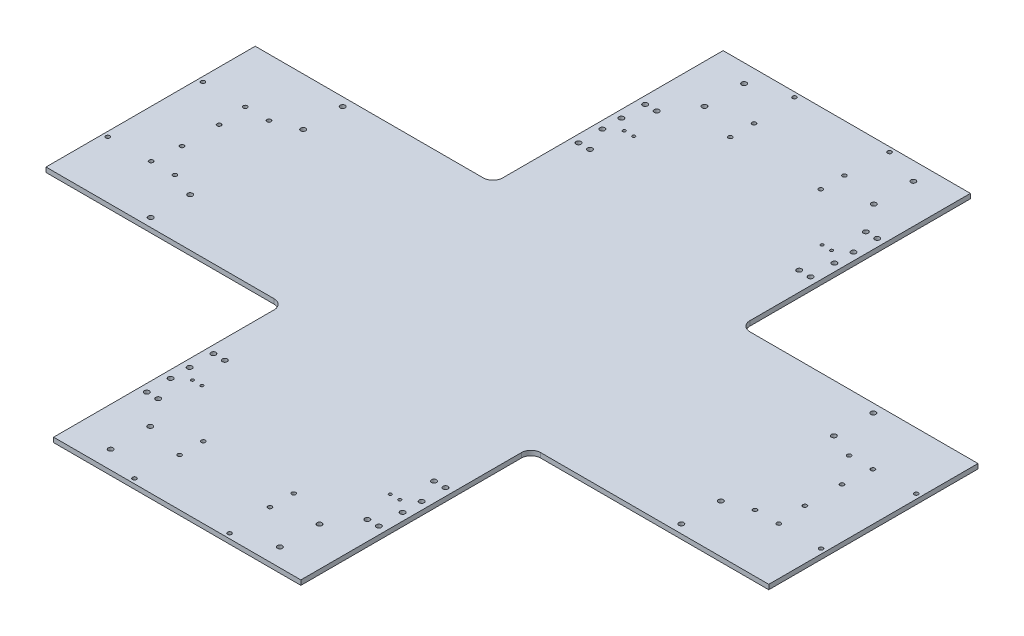
SolidWorks part; units mm, degrees
material "3.0205 (EN-AW 1200)"
ref_plane "前视基准面" through (0, 0, 0) normal (0, 0, 1) x (1, 0, 0)
ref_plane "上视基准面" through (0, 0, 0) normal (0, 1, 0) x (1, 0, 0)
ref_plane "右视基准面" through (0, 0, 0) normal (1, 0, 0) x (0, 0, -1)
other "Configuration Table"
sketch "Sketch1" plane through (0, 0, 0) normal (0, 1, 0) x (1, 0, 0)
  line L0 (130, 352) -> (-130, 352)
  line L1 (-130, 352) -> (-130, 110)
  line L2 (-130, 110) -> (-380, 110)
  line L5 (-380, 110) -> (-380, -110)
  line L6 (0, 352) -> (0, -66.8675) construction
  line L7 (-380, 0) -> (131.0517, 0) construction
  line L8 (380, 110) -> (380, -110)
  line L11 (130, 110) -> (380, 110)
  line L12 (130, 352) -> (130, 110)
  line L13 (130, -352) -> (130, -110)
  line L14 (130, -110) -> (380, -110)
  line L19 (-130, -110) -> (-380, -110)
  line L20 (-130, -352) -> (-130, -110)
  line L21 (130, -352) -> (-130, -352)
  point P21 (380, 0)
  dimension "D1" = 130
  dimension "D2" = 250
  dimension "D3" = 110
  dimension "D4" = 242
extrude "Boss-Extrude1" add sketch "Sketch1" along normal blind 5
sketch "Sketch2" plane through (0, 5, 0) normal (0, 1, 0) x (1, 0, 0)
  line L2 (380, 110) -> (130, 110) construction
  line L3 (380, -110) -> (380, 110) construction
  line L4 (-56.7455, 0) -> (47.5165, 0) construction
  line L5 (0, 54.7142) -> (0, -64.2255) construction
  line L6 (130, 110) -> (130, 352) construction
  line L7 (130, 352) -> (-130, 352) construction
  circle A0 centre (330, 49.5) radius 2.125
  circle A1 centre (305, 49.5) radius 2.125
  circle A2 centre (327.5, 19.5) radius 2.125
  circle A6 centre (327.5, -19.5) radius 2.125
  circle A7 centre (305, -49.5) radius 2.125
  circle A8 centre (330, -49.5) radius 2.125
  circle A9 centre (-330, -49.5) radius 2.125
  circle A10 centre (-305, -49.5) radius 2.125
  circle A11 centre (-327.5, -19.5) radius 2.125
  circle A12 centre (-327.5, 19.5) radius 2.125
  circle A13 centre (-305, 49.5) radius 2.125
  circle A14 centre (-330, 49.5) radius 2.125
  circle A15 centre (47.5, 302) radius 2.125
  circle A16 centre (47.5, 277) radius 2.125
  circle A17 centre (-47.5, 277) radius 2.125
  circle A18 centre (-47.5, 302) radius 2.125
  circle A19 centre (-47.5, -302) radius 2.125
  circle A20 centre (-47.5, -277) radius 2.125
  circle A21 centre (47.5, -277) radius 2.125
  circle A22 centre (47.5, -302) radius 2.125
  dimension "D1" = 60.5
  dimension "D3" = 52.5
  dimension "D5" = 4.25
  dimension "D7" = 4.25
  dimension "D8" = 4.25
  dimension "D9" = 4.25
  dimension "D10" = 4.25
  dimension "D2" = 90.5
  dimension "D4" = 25
  dimension "D6" = 50
  dimension "D11" = 82.5
  dimension "D12" = 50
  dimension "D13" = 25
extrude "Cut-Extrude1" cut sketch "Sketch2" against normal blind 3
sketch "Sketch4" plane through (0, 5, 0) normal (0, 1, 0) x (1, 0, 0)
  line L0 (-130, 352) -> (-130, 110) construction
  line L1 (130, 352) -> (-130, 352) construction
  line L2 (0, 46.9886) -> (0, -40.2904) construction
  line L3 (-35.103, 0) -> (92.4951, 0) construction
  line L5 (130, -352) -> (130, -110) construction
  circle A0 centre (-122, 192) radius 2.6
  circle A1 centre (-110, 192) radius 2.6
  circle A2 centre (-122, 217) radius 2.6
  circle A3 centre (-122, 237) radius 2.6
  circle A4 centre (-122, 262) radius 2.6
  circle A5 centre (-110, 262) radius 2.6
  circle A6 centre (110, 262) radius 2.6
  circle A7 centre (122, 262) radius 2.6
  circle A8 centre (122, 237) radius 2.6
  circle A9 centre (122, 217) radius 2.6
  circle A10 centre (110, 192) radius 2.6
  circle A11 centre (122, 192) radius 2.6
  circle A12 centre (122, -192) radius 2.6
  circle A13 centre (110, -192) radius 2.6
  circle A14 centre (122, -217) radius 2.6
  circle A15 centre (122, -237) radius 2.6
  circle A16 centre (122, -262) radius 2.6
  circle A17 centre (110, -262) radius 2.6
  circle A18 centre (-110, -262) radius 2.6
  circle A19 centre (-122, -262) radius 2.6
  circle A20 centre (-122, -237) radius 2.6
  circle A21 centre (-122, -217) radius 2.6
  circle A22 centre (-110, -192) radius 2.6
  circle A23 centre (-122, -192) radius 2.6
  circle A24 centre (109, -227) radius 1.6
  circle A25 centre (-109, -227) radius 1.6
  circle A26 centre (109, 227) radius 1.6
  circle A27 centre (-109, 227) radius 1.6
  circle A28 centre (99, -227) radius 1.6
  circle A29 centre (-99, -227) radius 1.6
  circle A30 centre (99, 227) radius 1.6
  circle A31 centre (-99, 227) radius 1.6
  dimension "D3" = 5.2
  dimension "D4" = 5.2
  dimension "D5" = 8
  dimension "D6" = 8
  dimension "D9" = 5.2
  dimension "D10" = 5.2
  dimension "D11" = 5.2
  dimension "D12" = 5.2
  dimension "D19" = 3.2
  dimension "D20" = 21
  dimension "D21" = 10
  dimension "D22" = 3.2
  dimension "D23" = 10
  dimension "D1" = 8
  dimension "D2" = 20
  dimension "D7" = 8
  dimension "D8" = 20
  dimension "D13" = 25
  dimension "D14" = 20
  dimension "D15" = 25
  dimension "D16" = 25
  dimension "D17" = 90
  dimension "D18" = 0
extrude "Cut-Extrude3" cut sketch "Sketch4" against normal blind 10
sketch "Sketch5" plane through (0, 5, 0) normal (0, 1, 0) x (1, 0, 0)
  line L0 (130, 352) -> (-130, 352) construction
  line L2 (-130, 352) -> (-130, 110) construction
  line L4 (130, 110) -> (130, 352) construction
  line L5 (-46.9195, 0) -> (66.6223, 0) construction
  line L6 (0, 59.0569) -> (0, -54.4849) construction
  line L10 (-380, 110) -> (-380, -110) construction
  line L12 (-130, 110) -> (-380, 110) construction
  line L13 (-380, -110) -> (-130, -110) construction
  circle A0 centre (-50, 347) radius 2.1
  circle A1 centre (50, 347) radius 2.1
  circle A2 centre (50, -347) radius 2.1
  circle A3 centre (-50, -347) radius 2.1
  circle A4 centre (-375, 50) radius 2.1
  circle A5 centre (-375, -50) radius 2.1
  circle A6 centre (375, -50) radius 2.1
  circle A7 centre (375, 50) radius 2.1
  dimension "D1" = 4.2
  dimension "D2" = 4.2
  dimension "D3" = 60
  dimension "D6" = 4.2
  dimension "D7" = 4.2
  dimension "5" = 5
  dimension "D4" = 80
  dimension "D5" = 80
  dimension "D8" = 60
  dimension "D9" = 5
  dimension "D10" = 5
extrude "Cut-Extrude4" cut sketch "Sketch5" against normal blind 10
fillet "Fillet1" radius 10 4 edges at (-130, 2.5, -110) (-130, 2.5, 110) (130, 2.5, 110) (130, 2.5, -110)
sketch "Sketch6" plane through (0, 5, 0) normal (0, 1, 0) x (1, 0, 0)
  line L0 (130, 352) -> (-130, 352) construction
  line L2 (130, 120) -> (130, 352) construction
  line L3 (-64.416, 0) -> (103.2752, 0) construction
  line L4 (0, 86.0771) -> (0, -73.7041) construction
  line L5 (380, 110) -> (140, 110) construction
  line L6 (380, -110) -> (380, 110) construction
  circle A0 centre (89, 333) radius 2.6
  circle A1 centre (89, 291.4) radius 2.6
  circle A2 centre (89, -291.4) radius 2.6
  circle A3 centre (89, -333) radius 2.6
  circle A4 centre (-89, -333) radius 2.6
  circle A5 centre (-89, -291.4) radius 2.6
  circle A6 centre (-89, 291.4) radius 2.6
  circle A7 centre (-89, 333) radius 2.6
  circle A8 centre (279, 101) radius 2.6
  circle A9 centre (279, 59.4) radius 2.6
  circle A10 centre (279, -59.4) radius 2.6
  circle A11 centre (279, -101) radius 2.6
  circle A12 centre (-279, -101) radius 2.6
  circle A13 centre (-279, -59.4) radius 2.6
  circle A14 centre (-279, 59.4) radius 2.6
  circle A15 centre (-279, 101) radius 2.6
  dimension "D1" = 5.2
  dimension "D2" = 5.2
  dimension "D6" = 5.2
  dimension "D7" = 5.2
  dimension "D3" = 19
  dimension "D4" = 41
  dimension "D5" = 41.6
  dimension "D8" = 9
  dimension "D9" = 41.6
  dimension "D10" = 101
extrude "Cut-Extrude5" cut sketch "Sketch6" against normal blind 10
